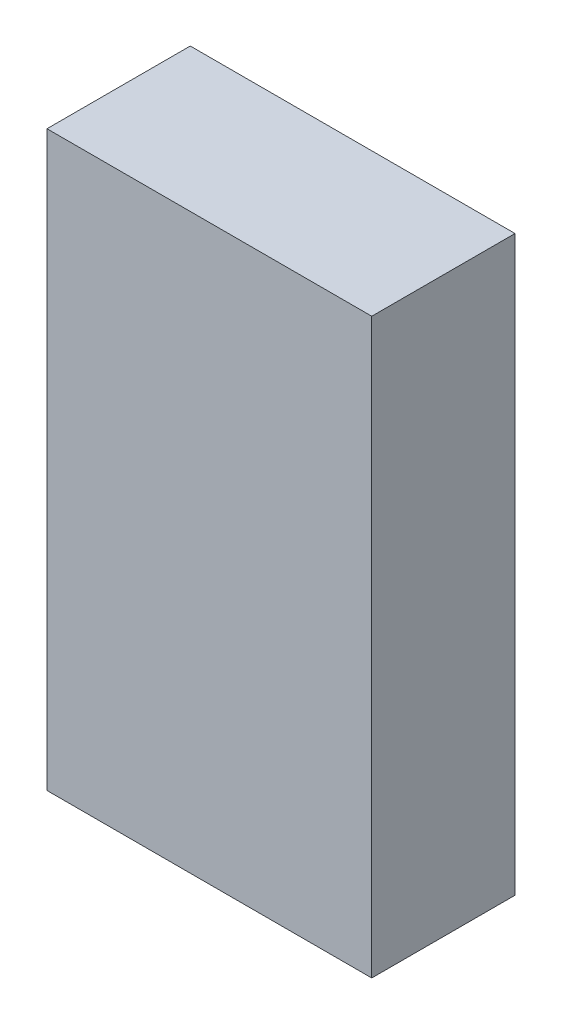
SolidWorks part; units mm, degrees
material "AISI 304"
ref_plane "Alzado" through (0, 0, 0) normal (0, 0, 1) x (1, 0, 0)
ref_plane "Planta" through (0, 0, 0) normal (0, 1, 0) x (1, 0, 0)
ref_plane "Vista lateral" through (0, 0, 0) normal (1, 0, 0) x (0, 0, -1)
sketch "Croquis1" plane through (0, 0, 0) normal (0, 0, 1) x (1, 0, 0)
  line L1 (-8.5, -15) -> (8.5, -15)
  line L2 (-8.5, -15) -> (-8.5, 15)
  line L3 (-8.5, 15) -> (8.5, 15)
  line L4 (8.5, -15) -> (8.5, 15)
  line L5 (-8.5, -15) -> (8.5, 15) construction
  line L6 (-8.5, 15) -> (8.5, -15) construction
  point P1 (0, 0)
  dimension "D1" = 30
  dimension "D2" = 17
extrude "Saliente-Extruir1" add sketch "Croquis1" along normal blind 7.5
